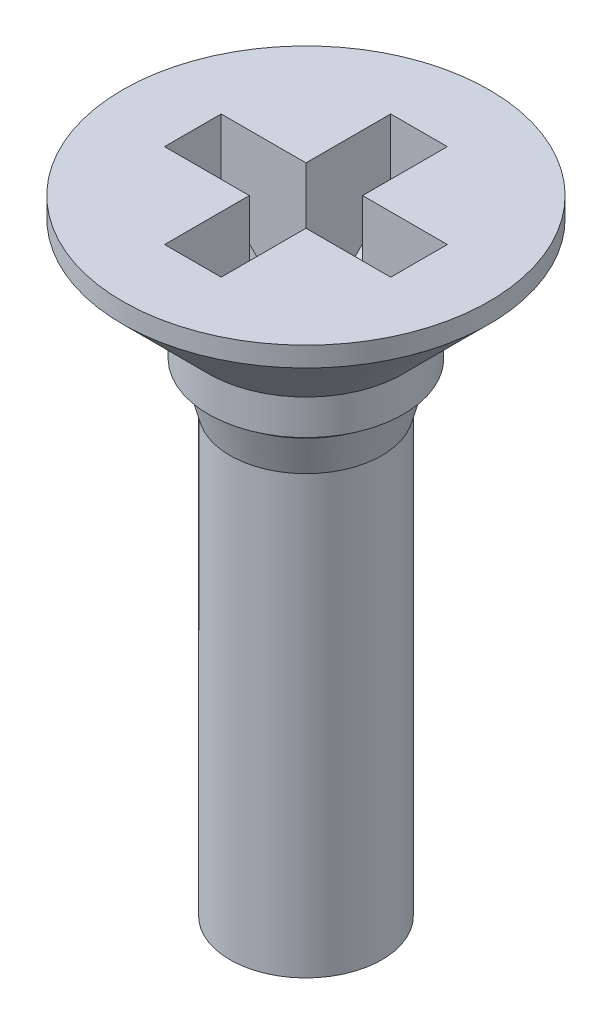
SolidWorks part; units mm, degrees
ref_plane "Vorderseite" through (0, 0, 0) normal (0, 0, 1) x (1, 0, 0)
ref_plane "Oben" through (0, 0, 0) normal (0, 1, 0) x (1, 0, 0)
ref_plane "Rechts" through (0, 0, 0) normal (1, 0, 0) x (0, 0, -1)
sketch "Skizze1" plane through (0, 0, 0) normal (0, 0, 1) x (1, 0, 0)
  line L0 (0, 0) -> (2.35, 0)
  line L1 (2.35, 0) -> (2.35, -0.254)
  line L2 (2.35, -0.254) -> (1.25, -1.354)
  line L3 (1.104, -1.804) -> (1.104, -1.9148)
  line L4 (1.104, -1.9148) -> (0.974, -2.4)
  line L5 (0.974, -2.4) -> (0.974, -8)
  line L6 (0.974, -8) -> (0, -8)
  line L7 (0, 0) -> (0, -8) construction
  line L8 (0, 0) -> (0, -8)
  line L10 (1.25, -1.354) -> (1.25, -1.804)
  line L12 (1.25, -1.804) -> (1.104, -1.804)
  point P3 (1.104, -1.5)
  dimension "D1" = 45
  dimension "D2" = 15
  dimension "K" = 1.5
  dimension "DA" = 4.7
  dimension "DK" = 1.948
  dimension "L" = 8
  dimension "DG" = 2.5
  dimension "A" = 0.9
  dimension "DF" = 2.208
  dimension "P" = 0.45
revolve "Basis-Rotation" add sketch "Skizze1" angle 360 about L7
sketch "Skizze2" plane through (0, 0, 0) normal (0, 0, 1) x (1, 0, 0)
  line L0 (0, -1.8) -> (0, 0) construction
  line L1 (0, 0) -> (0, -8) construction
  line L2 (-0.55, -1.8) -> (0.55, -1.8)
  line L3 (1.45, 0) -> (1.45, -0.9)
  line L4 (1.45, -0.9) -> (0.55, -1.8)
  line L5 (1.45, 0) -> (-1.45, 0)
  line L6 (-1.45, -0.9) -> (-0.55, -1.8)
  line L7 (-1.45, 0) -> (-1.45, -0.9)
  line L8 (0, -0.9) -> (1.45, -0.9) construction
  line L9 (2.35, 0) -> (-2.35, 0) construction
  line L11 (1.25, -1.354) -> (2.35, -0.254) construction
  point P11 (0, 0)
  dimension "M" = 2.9
  dimension "T" = 1.8
extrude "Kreuzschlitz1 H" cut sketch "Skizze2" against normal blind 0.363 and the other way blind 0.363
sketch "Skizze3" plane through (0, 0, 0) normal (1, 0, 0) x (0, 0, -1)
  line L0 (0, -1.8) -> (0, 0) construction
  line L2 (-0.55, -1.8) -> (0.55, -1.8)
  line L3 (1.45, 0) -> (1.45, -0.9)
  line L4 (1.45, -0.9) -> (0.55, -1.8)
  line L5 (1.45, 0) -> (-1.45, 0)
  line L6 (-1.45, -0.9) -> (-0.55, -1.8)
  line L7 (-1.45, 0) -> (-1.45, -0.9)
  line L8 (0, -0.9) -> (1.45, -0.9) construction
  point P11 (0, 0)
extrude "Kreuzschlitz2 H" cut sketch "Skizze3" against normal blind 0.363 and the other way blind 0.363
sketch "Skizze4" plane through (2.4522, 0, -1.8507) normal (0, 1, 0) x (-1, 0, 0)
  line L0 (7.3522, 1.8507) -> (-2.4478, 1.8507) construction
  line L1 (2.4522, -3.0493) -> (2.4522, 6.7507) construction
  line L2 (-2.4478, 1.0342) -> (-2.4478, 2.6672)
  line L3 (-2.4478, 1.0342) -> (0.0059, 1.0342)
  line L4 (0.0059, 1.0342) -> (0.8191, 0.6258)
  line L5 (1.2273, 0.2176) -> (-1.0126, -1.6141)
  line L6 (0.8191, 0.6258) -> (-1.0126, -1.6141)
  line L7 (1.6357, -0.5956) -> (1.2273, 0.2176)
  line L8 (1.6357, -3.0493) -> (1.6357, -0.5956)
  line L9 (1.6357, -3.0493) -> (3.2687, -3.0493)
  line L10 (3.2687, -3.0493) -> (3.2687, -0.5956)
  line L11 (3.2687, -0.5956) -> (3.6772, 0.2176)
  line L12 (2.4522, 1.8507) -> (-1.0126, -1.6141) construction
  line L13 (4.0854, 0.6258) -> (5.917, -1.6141)
  line L14 (3.6772, 0.2176) -> (5.917, -1.6141)
  line L15 (4.8986, 1.0342) -> (4.0854, 0.6258)
  line L16 (7.3522, 1.0342) -> (4.8986, 1.0342)
  line L17 (7.3522, 1.0342) -> (7.3522, 2.6672)
  line L18 (7.3522, 2.6672) -> (4.8986, 2.6672)
  line L19 (4.8986, 2.6672) -> (4.0854, 3.0757)
  line L20 (3.6772, 3.4839) -> (5.917, 5.3156)
  line L21 (4.0854, 3.0757) -> (5.917, 5.3156)
  line L22 (3.2687, 4.2971) -> (3.6772, 3.4839)
  line L23 (3.2687, 6.7507) -> (3.2687, 4.2971)
  line L24 (1.6357, 6.7507) -> (3.2687, 6.7507)
  line L25 (1.6357, 6.7507) -> (1.6357, 4.2971)
  line L26 (1.6357, 4.2971) -> (1.2273, 3.4839)
  line L27 (0.8191, 3.0757) -> (-1.0126, 5.3156)
  line L28 (1.2273, 3.4839) -> (-1.0126, 5.3156)
  line L29 (0.0059, 2.6672) -> (0.8191, 3.0757)
  line L30 (-2.4478, 2.6672) -> (0.0059, 2.6672)
  circle A0 centre (2.4522, 1.8507) radius 4.9 construction
  circle A1 centre (2.4522, 1.8507) radius 2.0415 construction
  circle A2 centre (2.4522, 1.8507) radius 2.579 construction
  dimension "X2" = 4.083
  dimension "X1" = 5.158
  dimension "M" = 9.8
  dimension "D3" = 5.725
  dimension "X3" = 1.633
